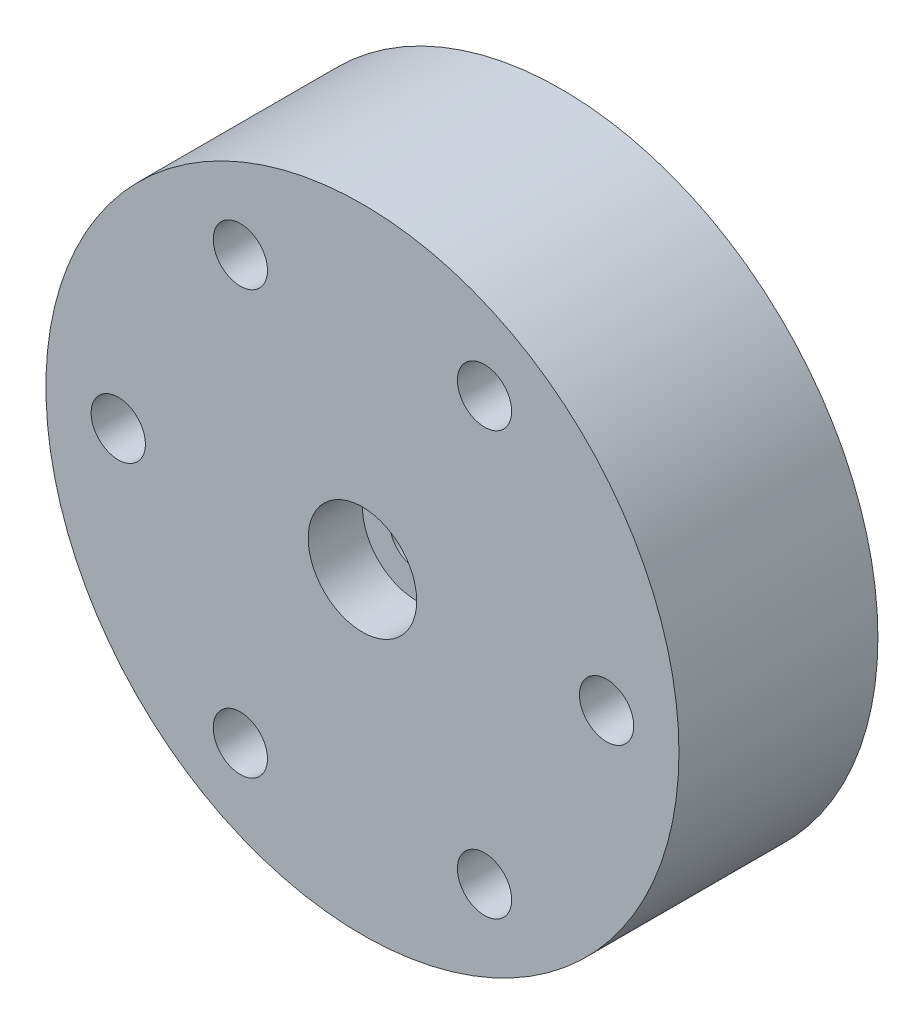
SolidWorks part; units mm, degrees
ref_plane "前视基准面" through (0, 0, 0) normal (0, 0, 1) x (1, 0, 0)
ref_plane "上视基准面" through (0, 0, 0) normal (0, 1, 0) x (1, 0, 0)
ref_plane "右视基准面" through (0, 0, 0) normal (1, 0, 0) x (0, 0, -1)
other "Configuration Table"
sketch "草图1" plane through (0, 0, 0) normal (0, 0, 1) x (1, 0, 0)
  circle A0 centre (0, 0) radius 17.5
  dimension "D1" = 35
extrude "凸台-拉伸1" add sketch "草图1" along normal blind 11
sketch "草图2" plane through (0, 0, 11) normal (0, 0, 1) x (1, 0, 0)
  circle A0 centre (13.5, 0) radius 1.5
  dimension "D2" = 3
  dimension "D1" = 13.5
extrude "切除-拉伸1" cut sketch "草图2" against normal blind 5
pattern_circular "阵列(圆周)1" count 6 over 360 about axis through (0, 0, 0) along (0, 0, 1) of "切除-拉伸1"
sketch "草图3" plane through (0, 0, 11) normal (0, 0, 1) x (1, 0, 0)
  circle A0 centre (0, 0) radius 3
  dimension "D1" = 6
extrude "切除-拉伸2" cut sketch "草图3" against normal blind 3
sketch "草图4" plane through (0, 0, 8) normal (0, 0, 1) x (1, 0, 0)
  circle A0 centre (0, 0) radius 1.5
  dimension "D1" = 3
extrude "切除-拉伸3" cut sketch "草图4" against normal blind 5
